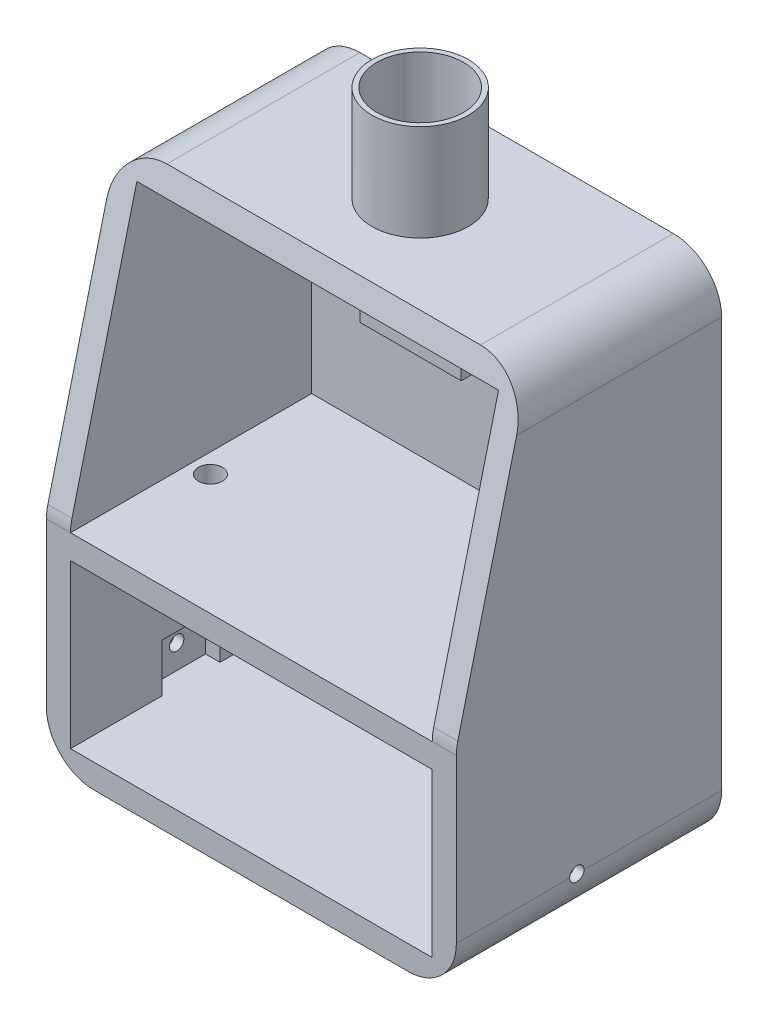
SolidWorks part; units mm, degrees
ref_plane "Front Plane" through (0, 0, 0) normal (0, 0, 1) x (1, 0, 0)
ref_plane "Top Plane" through (0, 0, 0) normal (0, 1, 0) x (1, 0, 0)
ref_plane "Right Plane" through (0, 0, 0) normal (1, 0, 0) x (0, 0, -1)
sketch "Sketch1" plane through (0, 0, 0) normal (0, 0, 1) x (1, 0, 0)
  line L1 (-35, -55) -> (30, -55)
  line L2 (-45, -45) -> (-45, 40)
  line L3 (-35, 50) -> (30, 50)
  line L4 (40, -45) -> (40, 40)
  line L5 (-40, -50) -> (35, -50)
  line L6 (-40, -50) -> (-40, 45)
  line L7 (-40, 45) -> (35, 45)
  line L8 (35, -50) -> (35, 45)
  arc A0 (-45, 40) -> (-35, 50) centre (-35, 40) cw
  arc A1 (30, 50) -> (40, 40) centre (30, 40) cw
  arc A2 (30, -55) -> (40, -45) centre (30, -45) ccw
  arc A3 (-35, -55) -> (-45, -45) centre (-35, -45) cw
  point P0 (0, 0)
  point P6 (0, 0)
  point P7 (0, 0)
  point P12 (0, 0)
  point P15 (-45, 50)
  point P18 (40, 50)
  point P21 (40, -55)
  dimension "D5" = 10
  dimension "D1" = 105
  dimension "D2" = 85
  dimension "D3" = 75
  dimension "D4" = 95
extrude "Boss-Extrude4" add sketch "Sketch1" along normal blind 50
sketch "Sketch5" plane through (0, 0, 0) normal (0, 0, -1) x (-1, 0, 0)
  line L5 (45, 40) -> (45, -45) construction
  line L6 (-30, -55) -> (35, -55)
  line L10 (-40, -45) -> (-40, 40)
  line L11 (-30, 50) -> (35, 50)
  line L12 (45, -45) -> (45, 40)
  line L13 (-40, -55) -> (45, 50) construction
  line L14 (-40, 50) -> (45, -55) construction
  line L15 (-30, 50) -> (35, 50) construction
  arc A4 (35, -55) -> (45, -45) centre (35, -45) ccw
  arc A5 (-30, -55) -> (-40, -45) centre (-30, -45) cw
  arc A6 (-40, 40) -> (-30, 50) centre (-30, 40) cw
  arc A7 (35, 50) -> (45, 40) centre (35, 40) cw
  point P0 (0, 0)
  point P1 (2.5, -2.5)
  point P7 (0, 0)
  dimension "D3" = 10
  dimension "D1" = 85
  dimension "D2" = 105
extrude "Boss-Extrude5" add sketch "Sketch5" along normal blind 5
sketch "Sketch7" plane through (35, 0, 0) normal (-1, 0, 0) x (0, 0, 1)
  line L5 (50, -50) -> (0, -50) construction
  circle A0 centre (25, -45) radius 1.5
  dimension "D1" = 3
  dimension "D2" = 5
extrude "Cut-Extrude4" cut sketch "Sketch7" against normal through all both and the other way through all
sketch "Sketch10" plane through (35, 0, 0) normal (-1, 0, 0) x (0, 0, 1)
  line L1 (19, -50) -> (31, -50)
  line L2 (19, -50) -> (19, -40)
  line L3 (19, -40) -> (31, -40)
  line L4 (31, -50) -> (31, -40)
  line L5 (19, -50) -> (31, -40) construction
  line L6 (19, -40) -> (31, -50) construction
  point P0 (25, -45)
  dimension "D1" = 12
  dimension "D2" = 10
extrude "Cut-Extrude5" cut sketch "Sketch10" against normal blind 3
sketch "Sketch11" plane through (-40, 0, 0) normal (1, 0, 0) x (0, 0, -1)
  line L1 (-31, -50) -> (-19, -50)
  line L2 (-31, -50) -> (-31, -40)
  line L3 (-31, -40) -> (-19, -40)
  line L4 (-19, -50) -> (-19, -40)
  line L5 (-31, -50) -> (-19, -40) construction
  line L6 (-31, -40) -> (-19, -50) construction
  point P0 (-25, -45)
  dimension "D1" = 12
  dimension "D2" = 10
extrude "Cut-Extrude6" cut sketch "Sketch11" against normal blind 3
sketch "Sketch12" plane through (40, 0, 0) normal (1, 0, 0) x (0, 0, -1)
  line L0 (-50, -10) -> (-35, 50)
  line L1 (-50, -45) -> (-50, 40) construction
  line L2 (-50, 50) -> (5, 50) construction
  line L3 (-35, 50) -> (-50, 50)
  line L4 (-50, 50) -> (-50, -10)
  dimension "D1" = 35
  dimension "D2" = 15
extrude "Cut-Extrude7" cut sketch "Sketch12" against normal through all
fillet "Fillet11" radius 10 2 edges at (37.5, -10, 50) (-42.5, -10, 50)
sketch "Sketch13" plane through (-40, 0, 0) normal (1, 0, 0) x (0, 0, -1)
  line L6 (-50, -11.2311) -> (0, -11.2311)
  line L7 (-50, -11.2311) -> (-50, -16.2311)
  line L8 (-50, -16.2311) -> (0, -16.2311)
  line L9 (0, -11.2311) -> (0, -16.2311)
  dimension "D1" = 5
extrude "Boss-Extrude7" add sketch "Sketch13" along normal blind 75
sketch "Sketch17" plane through (0, 0, 0) normal (0, 0, 1) x (1, 0, 0)
  line L0 (-40, -16.2311) -> (-40, -50) construction
  line L1 (35, -16.2311) -> (-40, -16.2311) construction
  circle A0 centre (-2.5, -26.7311) radius 1.5
  dimension "D1" = 3
  dimension "D2" = 37.5
  dimension "D3" = 10.5
extrude "Cut-Extrude9" cut sketch "Sketch17" against normal blind 5
sketch "Sketch18" plane through (0, 0, 0) normal (0, 0, 1) x (1, 0, 0)
  line L1 (-13, 28.5609) -> (8, 28.5609)
  line L2 (-13, 28.5609) -> (-13, 23.5609)
  line L3 (-13, 23.5609) -> (8, 23.5609)
  line L4 (8, 28.5609) -> (8, 23.5609)
  line L5 (-13, 28.5609) -> (8, 23.5609) construction
  line L6 (-13, 23.5609) -> (8, 28.5609) construction
  line L9 (-40, 45) -> (-40, -11.2311) construction
  point P0 (-2.5, 26.0609)
  dimension "D1" = 21
  dimension "D2" = 5
  dimension "D3" = 37.5
extrude "Boss-Extrude8" add sketch "Sketch18" along normal blind 17
sketch "Sketch21" plane through (0, -11.2311, 0) normal (0, 1, 0) x (1, 0, 0)
  line L0 (35, 0) -> (35, -50) construction
  line L1 (-40, 0) -> (-40, -50) construction
  circle A0 centre (-36, -24.9909) radius 2.5
  circle A1 centre (31, -24.9909) radius 2.5
  dimension "D2" = 5
  dimension "D3" = 5
  dimension "D1" = 4
  dimension "D4" = 4
extrude "Cut-Extrude10" cut sketch "Sketch21" against normal blind 17
sketch "Sketch22" plane through (0, 50, 0) normal (0, 1, 0) x (1, 0, 0)
  circle A0 centre (-2.5, -15) radius 10
  circle A1 centre (-2.5, -15) radius 9
  dimension "D1" = 20
  dimension "D2" = 18
extrude "Boss-Extrude9" add sketch "Sketch22" along normal blind 20
sketch "Sketch24" plane through (0, 50, 0) normal (0, 1, 0) x (1, 0, 0)
  circle A0 centre (-2.5, -15) radius 9
extrude "Cut-Extrude11" cut sketch "Sketch24" against normal blind 5
